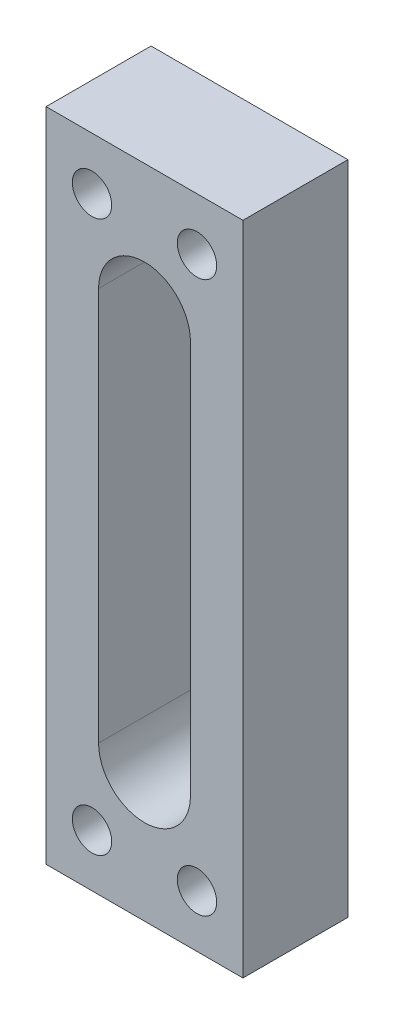
SolidWorks part; units mm, degrees
material "POM 乙缩醛共聚物"
ref_plane "前视基准面" through (0, 0, 0) normal (0, 0, 1) x (1, 0, 0)
ref_plane "上视基准面" through (0, 0, 0) normal (0, 1, 0) x (1, 0, 0)
ref_plane "右视基准面" through (0, 0, 0) normal (1, 0, 0) x (0, 0, -1)
sketch "草图1" plane through (0, 0, 0) normal (0, 0, 1) x (1, 0, 0)
  line L1 (-7.5, 25) -> (7.5, 25)
  line L2 (-7.5, 25) -> (-7.5, -25)
  line L3 (-7.5, -25) -> (7.5, -25)
  line L4 (7.5, 25) -> (7.5, -25)
  line L5 (-7.5, 25) -> (7.5, -25) construction
  line L6 (-7.5, -25) -> (7.5, 25) construction
  point P0 (0, 0)
  dimension "D1" = 15
  dimension "D2" = 50
extrude "凸台-拉伸1" add sketch "草图1" along normal blind 8
sketch "草图2" plane through (0, 0, 8) normal (0, 0, 1) x (1, 0, 0)
  line L1 (-4, 21) -> (4, 21) construction
  line L2 (-4, 21) -> (-4, -21) construction
  line L3 (-4, -21) -> (4, -21) construction
  line L4 (4, 21) -> (4, -21) construction
  line L5 (-4, 21) -> (4, -21) construction
  line L6 (-4, -21) -> (4, 21) construction
  circle A0 centre (-4, 21) radius 1.5
  circle A1 centre (4, 21) radius 1.5
  circle A2 centre (4, -21) radius 1.5
  circle A3 centre (-4, -21) radius 1.5
  point P0 (0, 0)
  dimension "D3" = 3
  dimension "D1" = 42
  dimension "D2" = 8
extrude "切除-拉伸1" cut sketch "草图2" against normal through all
sketch "草图3" plane through (0, 0, 8) normal (0, 0, 1) x (1, 0, 0)
  line L0 (0, 25) -> (0, -25) construction
  line L5 (7.5, 25) -> (-7.5, 25) construction
  line L6 (-7.5, -25) -> (7.5, -25) construction
  line L7 (0, 15) -> (0, -15) construction
  line L8 (3.5, 15) -> (3.5, -15)
  line L9 (-3.5, 15) -> (-3.5, -15)
  arc A0 (3.5, 15) -> (-3.5, 15) centre (0, 15) ccw
  arc A1 (-3.5, -15) -> (3.5, -15) centre (0, -15) ccw
  point P9 (0, 0)
  point P14 (0, 0)
  dimension "D1" = 3.5
  dimension "D2" = 30
extrude "切除-拉伸3" cut sketch "草图3" against normal through all
